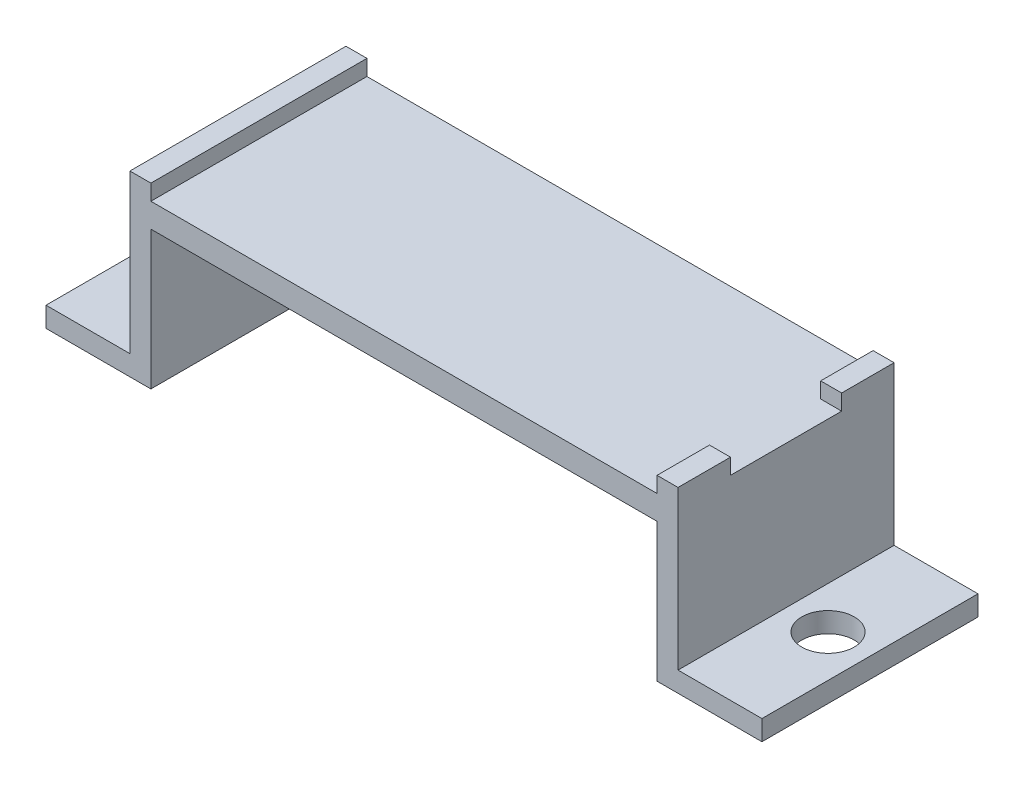
SolidWorks part; units mm, degrees
ref_plane "Plano frontal" through (0, 0, 0) normal (0, 0, 1) x (1, 0, 0)
ref_plane "Plano superior" through (0, 0, 0) normal (0, 1, 0) x (1, 0, 0)
ref_plane "Plano direito" through (0, 0, 0) normal (1, 0, 0) x (0, 0, -1)
sketch "Esboço1" plane through (0, 0, 0) normal (0, 0, 1) x (1, 0, 0)
  line L4 (35.3009, -9.9821) -> (-32.9591, -9.9821)
  line L5 (-32.9591, -9.9821) -> (-32.9591, -8.0641)
  line L6 (-32.9591, -8.0641) -> (-24.9591, -8.0641)
  line L8 (27.3009, -8.0641) -> (35.3009, -8.0641)
  line L9 (-24.9591, 5.5179) -> (27.3009, 5.5179)
  line L10 (-24.9591, 5.5179) -> (-24.9591, -8.0641)
  line L12 (27.3009, 5.5179) -> (27.3009, -8.0641)
  line L13 (35.3009, -8.0641) -> (35.3009, -9.9821)
  dimension "D1" = 15.5
  dimension "D2" = 8
  dimension "D3" = 8
extrude "Ressalto-extrusão1" add sketch "Esboço1" along normal blind 20.6
sketch "Esboço2" plane through (0, 0, 20.6) normal (0, 0, 1) x (1, 0, 0)
  line L0 (-32.9591, -9.9821) -> (35.3009, -9.9821) construction
  line L1 (-22.9591, -9.9821) -> (25.3009, -9.9821)
  line L2 (-22.9591, -9.9821) -> (-22.9591, 3.2179)
  line L3 (-22.9591, 3.2179) -> (25.3009, 3.2179)
  line L4 (25.3009, -9.9821) -> (25.3009, 3.2179)
  line L7 (-24.9591, 5.5179) -> (-24.9591, -8.0641) construction
  line L8 (27.3009, -8.0641) -> (27.3009, 5.5179) construction
  dimension "D1" = 13.2
  dimension "D2" = 2
  dimension "D3" = 2
extrude "Corte-extrusão1" cut sketch "Esboço2" against normal blind 25.4
sketch "Esboço3" plane through (-24.9591, 0, 0) normal (-1, 0, 0) x (0, 0, 1)
  line L1 (0, 5.5179) -> (20.6, 5.5179)
  line L2 (0, 5.5179) -> (0, 7.0179)
  line L3 (0, 7.0179) -> (20.6, 7.0179)
  line L4 (20.6, 5.5179) -> (20.6, 7.0179)
  dimension "D1" = 1.5
extrude "Ressalto-extrusão2" add sketch "Esboço3" against normal blind 2
sketch "Esboço4" plane through (27.3009, 0, 0) normal (1, 0, 0) x (0, 0, -1)
  line L0 (-20.6, 7.0179) -> (0, 7.0179) construction
  line L1 (-20.6, 5.5179) -> (-15.6, 5.5179)
  line L2 (-20.6, 5.5179) -> (-20.6, 7.0179)
  line L3 (-20.6, 7.0179) -> (-15.6, 7.0179)
  line L4 (-15.6, 5.5179) -> (-15.6, 7.0179)
  line L6 (0, 5.5179) -> (-5, 5.5179)
  line L7 (0, 5.5179) -> (0, 7.0179)
  line L8 (0, 7.0179) -> (-5, 7.0179)
  line L9 (-5, 5.5179) -> (-5, 7.0179)
  dimension "D1" = 5
  dimension "D2" = 5
extrude "Ressalto-extrusão3" add sketch "Esboço4" against normal blind 2
sketch "Esboço5" plane through (0, -8.0641, 0) normal (0, 1, 0) x (1, 0, 0)
  line L0 (35.3009, 0) -> (27.3009, -20.6) construction
  line L1 (27.3009, -20.6) -> (35.3009, -20.6) construction
  line L2 (35.3009, -20.6) -> (27.3009, 0) construction
  line L3 (27.3009, 0) -> (-24.9591, 0) construction
  line L4 (-24.9591, 0) -> (-32.9591, -20.6) construction
  line L5 (-32.9591, -20.6) -> (-32.9591, 0) construction
  line L6 (-32.9591, 0) -> (-24.9591, -20.6) construction
  circle A0 centre (-28.9591, -10.3) radius 2.5
  circle A1 centre (31.3009, -10.3) radius 2.5
extrude "Corte-extrusão2" cut sketch "Esboço5" against normal blind 2
